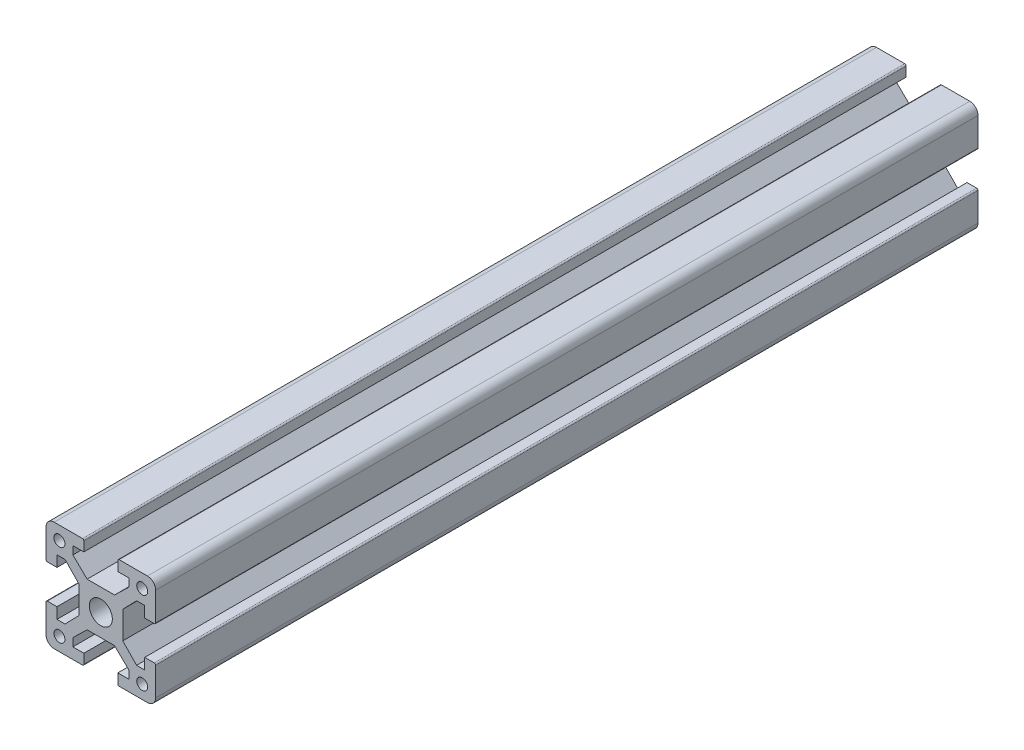
SolidWorks part; units mm, degrees
ref_plane "Front Plane" through (0, 0, 0) normal (0, 0, 1) x (1, 0, 0)
ref_plane "Top Plane" through (0, 0, 0) normal (0, 1, 0) x (1, 0, 0)
ref_plane "Right Plane" through (0, 0, 0) normal (1, 0, 0) x (0, 0, -1)
sketch "Sketch1" plane through (0, 0, 0) normal (0, 0, 1) x (1, 0, 0)
  line L88 (-6.4, -1.5) -> (-6.4, -6.65)
  line L89 (-6.15, -6.9) -> (-4.4, -6.9)
  line L90 (-4.4, -6.9) -> (-4.4, -4.9)
  line L91 (-4.4, -4.9) -> (-2.9278, -4.9)
  line L92 (-2.9278, -4.9) -> (-0.4, -7.5)
  line L93 (-0.4, -7.5) -> (-0.4, -12.5)
  line L94 (-0.4, -12.5) -> (-2.9278, -15.1)
  line L95 (-2.9278, -15.1) -> (-4.4, -15.1)
  line L96 (-4.4, -15.1) -> (-4.4, -13.1)
  line L97 (-4.4, -13.1) -> (-6.15, -13.1)
  line L98 (-6.4, -13.35) -> (-6.4, -18.5)
  line L99 (-4.9, -20) -> (0.25, -20)
  line L100 (0.5, -19.75) -> (0.5, -18)
  line L101 (0.5, -18) -> (-1.5, -18)
  line L102 (-1.5, -18) -> (-1.5, -16.5278)
  line L103 (-1.5, -16.5278) -> (1.1, -14)
  line L104 (1.1, -14) -> (6.1, -14)
  line L105 (6.1, -14) -> (8.7, -16.5278)
  line L106 (8.7, -16.5278) -> (8.7, -18)
  line L107 (8.7, -18) -> (6.7, -18)
  line L108 (6.7, -18) -> (6.7, -19.75)
  line L109 (6.95, -20) -> (12.1, -20)
  line L110 (13.6, -18.5) -> (13.6, -13.35)
  line L111 (13.35, -13.1) -> (11.6, -13.1)
  line L112 (11.6, -13.1) -> (11.6, -15.1)
  line L113 (11.6, -15.1) -> (10.1278, -15.1)
  line L114 (10.1278, -15.1) -> (7.6, -12.5)
  line L115 (7.6, -12.5) -> (7.6, -7.5)
  line L116 (7.6, -7.5) -> (10.1278, -4.9)
  line L117 (10.1278, -4.9) -> (11.6, -4.9)
  line L118 (11.6, -4.9) -> (11.6, -6.9)
  line L119 (11.6, -6.9) -> (13.35, -6.9)
  line L120 (13.6, -6.65) -> (13.6, -1.5)
  line L121 (12.1, 0) -> (6.95, 0)
  line L122 (6.7, -0.25) -> (6.7, -2)
  line L123 (6.7, -2) -> (8.7, -2)
  line L124 (8.7, -2) -> (8.7, -3.4722)
  line L125 (8.7, -3.4722) -> (6.1, -6)
  line L126 (6.1, -6) -> (1.1, -6)
  line L127 (1.1, -6) -> (-1.5, -3.4722)
  line L128 (-1.5, -3.4722) -> (-1.5, -2)
  line L129 (-1.5, -2) -> (0.5, -2)
  line L130 (0.5, -2) -> (0.5, -0.25)
  line L131 (0.25, 0) -> (-4.9, 0)
  circle A0 centre (-3.95, -2.45) radius 1
  circle A1 centre (11.15, -2.45) radius 1
  circle A2 centre (-3.95, -17.55) radius 1
  circle A3 centre (11.15, -17.55) radius 1
  circle A4 centre (3.6, -10) radius 2.1
  arc A26 (-6.4, -6.65) -> (-6.15, -6.9) centre (-6.15, -6.65) ccw
  arc A27 (-6.15, -13.1) -> (-6.4, -13.35) centre (-6.15, -13.35) ccw
  arc A28 (-6.4, -18.5) -> (-4.9, -20) centre (-4.9, -18.5) ccw
  arc A29 (0.25, -20) -> (0.5, -19.75) centre (0.25, -19.75) ccw
  arc A30 (6.7, -19.75) -> (6.95, -20) centre (6.95, -19.75) ccw
  arc A31 (12.1, -20) -> (13.6, -18.5) centre (12.1, -18.5) ccw
  arc A32 (13.6, -13.35) -> (13.35, -13.1) centre (13.35, -13.35) ccw
  arc A33 (13.35, -6.9) -> (13.6, -6.65) centre (13.35, -6.65) ccw
  arc A34 (13.6, -1.5) -> (12.1, 0) centre (12.1, -1.5) ccw
  arc A35 (6.95, 0) -> (6.7, -0.25) centre (6.95, -0.25) ccw
  arc A36 (0.5, -0.25) -> (0.25, 0) centre (0.25, -0.25) ccw
  arc A37 (-4.9, 0) -> (-6.4, -1.5) centre (-4.9, -1.5) ccw
extrude "Boss-Extrude2" add sketch "Sketch1" along normal blind 150
